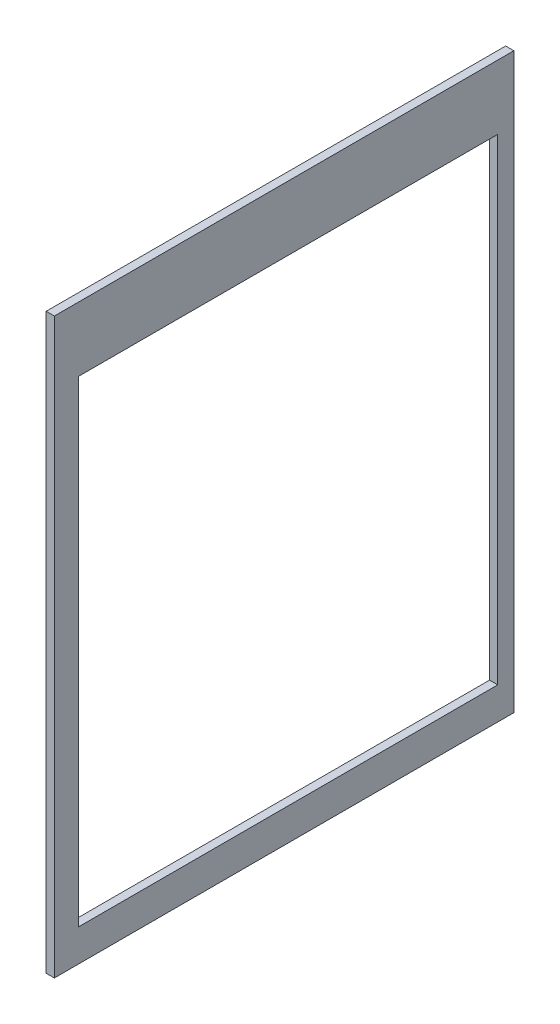
SolidWorks part; units mm, degrees
ref_plane "Alzado" through (0, 0, 0) normal (0, 0, 1) x (1, 0, 0)
ref_plane "Planta" through (0, 0, 0) normal (0, 1, 0) x (1, 0, 0)
ref_plane "Vista lateral" through (0, 0, 0) normal (1, 0, 0) x (0, 0, -1)
sketch "Croquis1" plane through (0, 0, 0) normal (1, 0, 0) x (0, 0, -1)
  line L8 (-389.3217, 326.7825) -> (-108.8217, 326.7825)
  line L11 (-389.3217, 326.7825) -> (-389.3217, -23.2175)
  line L17 (-389.3217, -23.2175) -> (-108.8217, -23.2175)
  line L39 (-108.8217, 326.7825) -> (-108.8217, -23.2175)
  line L40 (-118.6466, -3.5677) -> (-374.5844, -3.5677)
  line L41 (-118.6466, -3.5677) -> (-118.6466, 287.4831)
  line L42 (-118.6466, 287.4831) -> (-374.5844, 287.4831)
  line L43 (-374.5844, -3.5677) -> (-374.5844, 287.4831)
  dimension "D1" = 39.2995
  dimension "D2" = 19.6497
  dimension "D3" = 350
extrude "Saliente-Extruir2" add sketch "Croquis1" along normal blind 5
